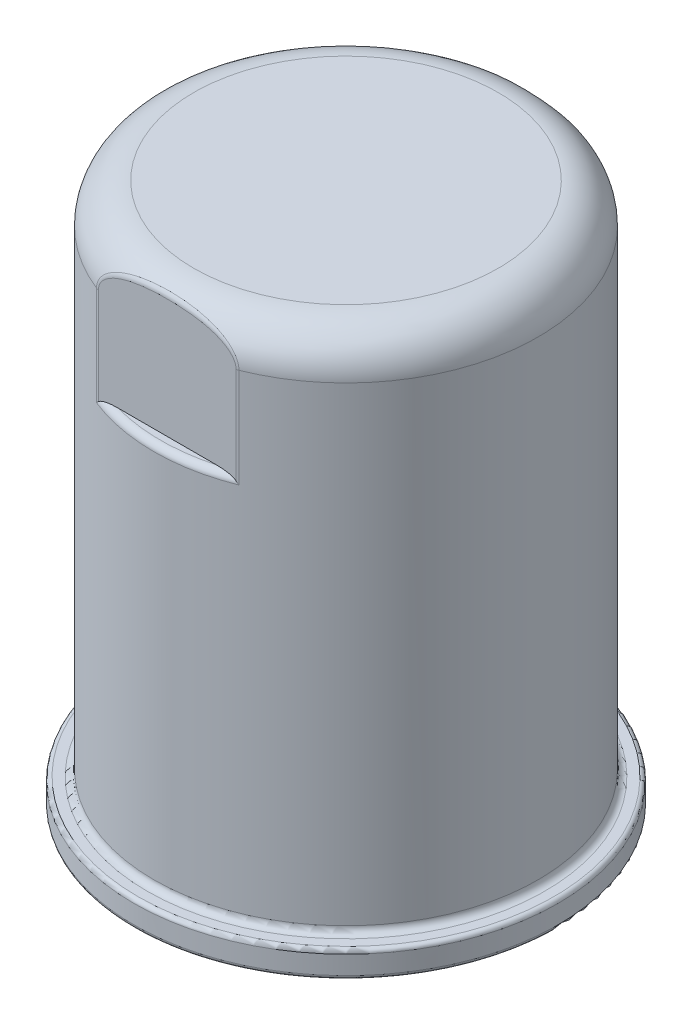
SolidWorks part; units mm, degrees
material "AISI 1010 Barra de acero laminada en caliente"
ref_plane "Alzado" through (0, 0, 0) normal (0, 0, 1) x (1, 0, 0)
ref_plane "Planta" through (0, 0, 0) normal (0, 1, 0) x (1, 0, 0)
ref_plane "Vista lateral" through (0, 0, 0) normal (1, 0, 0) x (0, 0, -1)
sketch "Croquis1" plane through (0, 0, 0) normal (0, 0, 1) x (1, 0, 0)
  line L0 (0, 0) -> (0, 41) construction
  line L1 (0, 41) -> (14.5, 41)
  line L2 (14.5, 41) -> (14.5, 2)
  line L3 (14.5, 0) -> (11.5, 0)
  line L4 (11.5, 0) -> (11.5, 21)
  line L5 (11.5, 21) -> (0, 21)
  line L6 (0, 21) -> (0, 41)
  line L7 (14.5, 0) -> (16, 0)
  line L8 (16, 0) -> (16, 2)
  line L9 (16, 2) -> (14.5, 2)
  dimension "D1" = 3
  dimension "D2" = 14.5
  dimension "D3" = 21
  dimension "D4" = 20
  dimension "D5" = 1.5
  dimension "D6" = 2
  dimension "D7" = 11.5
revolve "Revolución1" add sketch "Croquis1" angle 360 about L0
sketch "Croquis2" plane through (0, 21, 0) normal (0, -1, 0) x (1, 0, 0)
  point P0 (0, 0)
hole_wizard "Perforador para roscar Helicoil de M121" positions "Croquis4" profile "Croquis3" hole size "M12x1.75" standard "Ansi Metric"
sketch "Croquis4" plane through (0, 21, 0) normal (0, -1, 0) x (-1, 0, 0)
  point P0 (0, 0)
sketch "Croquis3" plane through (0, 21, 0) normal (1, 0, 0) x (0, 0, -1)
  line L0 (0, 0) -> (0, 13.0794)
  line L1 (0, 13.0794) -> (5.125, 10)
  line L2 (5.125, 10) -> (5.125, 0)
  line L5 (5.125, 0) -> (0, 0)
  line L10 (0, 13.0794) -> (-5.125, 10) construction
  line L11 (0, -6.35) -> (0, 107.95) construction
  dimension "Diámetro de taladro" = 10.25
  dimension "Profundidad de taladro" = 10
  dimension "Ángulo de perforador" = 118
thread "Rosca1" pitch 1.75 start angle 0, offset 0, length 10, pitch 1.75, diameter 10.25
ref_plane "Plano1" through (5.125, 21, 0) normal (0, 0, 1) x (1, 0, 0)
sketch "Perfil de rosca1" plane through (5.125, 21, 0) normal (0, 0, 1) x (1, 0, 0)
  line L0 (0, 0) -> (0, 1.75) construction
  line L1 (0, 0) -> (0.9472, 0.5469)
  line L2 (0.9472, 0.5469) -> (0.9472, 0.7656)
  line L3 (0.9472, 0.7656) -> (0, 1.3125)
  line L4 (0.9472, 0.6562) -> (0, 0.6562) construction
  line L11 (0, 0) -> (0, 1.3125)
  point P2 (0, 0)
  dimension "Pitch" = 1.75
  dimension "Profile_Angle" = 60
  dimension "Profile_Land" = 0.2188
  dimension "Profile_Height" = 0.9472
fillet "Redondeo1" radius 1 1 edges at (0, 0, -11.5)
fillet "Redondeo2" radius 0.3 2 edges at (0, 0, -16) (0, 2, -16)
fillet "Redondeo3" radius 0.5 1 edges at (0, 2, -14.5)
fillet "Redondeo4" radius 3 1 edges at (0, 41, -14.5)
sketch "Croquis5" plane through (0, 41, 0) normal (0, 1, 0) x (1, 0, 0)
  line L0 (-5.2915, 13.5) -> (5.2915, 13.5)
  line L1 (-5.2915, -13.5) -> (5.2915, -13.5)
  circle A0 centre (0, 0) radius 14.5 construction
  arc A1 (-5.2915, -13.5) -> (5.2915, -13.5) centre (0, 0) ccw
  arc A2 (5.2915, 13.5) -> (-5.2915, 13.5) centre (0, 0) ccw
  dimension "D1" = 13.5
  dimension "D2" = 27
extrude "Cortar-Extruir1" cut sketch "Croquis5" against normal blind 10
fillet "Redondeo5" radius 0.5 8 edges at (0, 31, -14.5) (0, 31, 14.5) (5.2915, 34.5, -13.5) (-5.2915, 34.5, -13.5) (-5.2915, 34.5, 13.5) (5.2915, 34.5, 13.5) (-1.0577, 35.8016, -13.5) (1.0577, 35.8016, 13.5)
